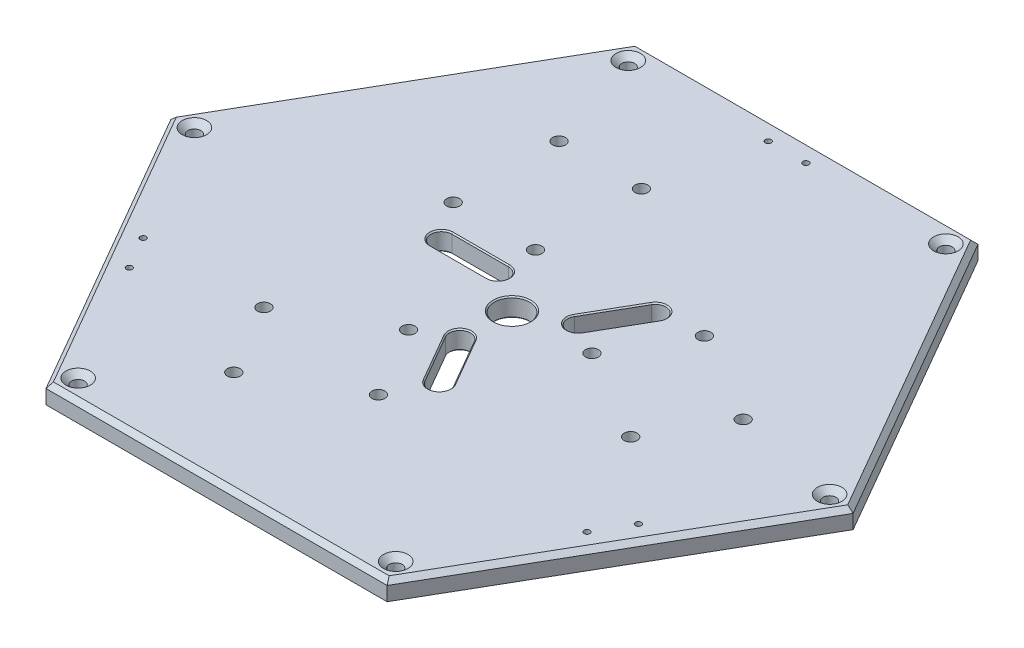
SolidWorks part; units mm, degrees
material "5052-H32"
ref_plane "Front Plane" through (0, 0, 0) normal (0, 0, 1) x (1, 0, 0)
ref_plane "Top Plane" through (0, 0, 0) normal (0, 1, 0) x (1, 0, 0)
ref_plane "Right Plane" through (0, 0, 0) normal (1, 0, 0) x (0, 0, -1)
sketch "Sketch1" plane through (0, 0, 0) normal (0, 1, 0) x (1, 0, 0)
  line L1 (72.5, 125.5737) -> (-72.5, 125.5737)
  line L2 (-72.5, 125.5737) -> (-145, 0)
  line L3 (-145, 0) -> (-72.5, -125.5737)
  line L4 (-72.5, -125.5737) -> (72.5, -125.5737)
  line L5 (72.5, -125.5737) -> (145, 0)
  line L6 (145, 0) -> (72.5, 125.5737)
  circle A0 centre (0, 0) radius 125.5737 construction
  dimension "D1" = 145
extrude "Boss-Extrude1" add sketch "Sketch1" along normal blind 8
sketch "Sketch2" plane through (0, 0, 0) normal (0, 1, 0) x (1, 0, 0)
  line L0 (0, 0) -> (108.75, 62.7868) construction
  line L1 (145, 0) -> (72.5, 125.5737) construction
  line L2 (69.5513, 20.4663) -> (52.0513, -9.8446) construction
  line L3 (69.0368, -25.4247) -> (30.0657, -2.9247) construction
  line L4 (66.5368, -29.7548) -> (27.5657, -7.2548) construction
  line L5 (53.4484, -16.4247) -> (43.4484, -33.7452) construction
  line L6 (32.5657, 1.4054) -> (71.5368, -21.0946) construction
  line L7 (71.5368, -21.0946) -> (89.0368, 9.2163) construction
  line L8 (89.0368, 9.2163) -> (50.0657, 31.7163) construction
  line L9 (50.0657, 31.7163) -> (32.5657, 1.4054) construction
  line L10 (-15.0657, -28.9054) -> (-54.0368, -51.4054) construction
  line L11 (2.4343, -59.2163) -> (-15.0657, -28.9054) construction
  line L12 (-36.5368, -81.7163) -> (2.4343, -59.2163) construction
  line L13 (-54.0368, -51.4054) -> (-36.5368, -81.7163) construction
  line L14 (-17.5, 27.5) -> (-17.5, 72.5) construction
  line L15 (-52.5, 27.5) -> (-17.5, 27.5) construction
  line L16 (-52.5, 72.5) -> (-52.5, 27.5) construction
  line L17 (-17.5, 72.5) -> (-52.5, 72.5) construction
  line L18 (43.4484, -33.7452) -> (35.6542, -29.2452) construction
  line L19 (52.0513, -9.8446) -> (43.3013, -25) construction
  line L20 (35.6542, -29.2452) -> (43.1542, -16.2548) construction
  line L21 (108.75, -62.7868) -> (0, 0) construction
  line L22 (72.5, -125.5737) -> (145, 0) construction
  point P9 (49.5513, -14.1747)
  point P18 (32.5657, 1.4054)
  point P19 (50.0657, 31.7163)
  point P20 (89.0368, 9.2163)
  point P21 (71.5368, -21.0946)
  point P31 (0, 0)
  point P33 (47.0513, -18.5048)
  point P36 (39.5513, -31.4952)
  point P39 (39.4042, -22.75)
  dimension "D1" = 45
  dimension "D2" = 35
  dimension "D4" = 5
  dimension "D5" = 5
  dimension "D6" = 50
  dimension "D7" = 20
  dimension "D8" = 9
  dimension "D3" = 3
sketch "Sketch5" plane through (0, 8, 0) normal (0, 1, 0) x (1, 0, 0)
  circle A0 centre (0, 0) radius 7.5
  dimension "D1" = 15
extrude "Cut-Extrude1" cut sketch "Sketch5" against normal through all
hole_wizard "CSK for M5 Flat Head Machine Screw1" positions "Sketch7" profile "Sketch6" countersink size "M5" standard "ANSI Metric" end condition through all
sketch "Sketch7" plane through (0, 0, 0) normal (0, -1, 0) x (-1, 0, 0)
  point P0 (52.5, 27.5)
  point P3 (17.5, 27.5)
  point P6 (17.5, 72.5)
  point P9 (52.5, 72.5)
  point P12 (-32.5657, 1.4054)
  point P15 (-71.5368, -21.0946)
  point P18 (-89.0368, 9.2163)
  point P21 (-50.0657, 31.7163)
  point P24 (15.0657, -28.9054)
  point P27 (-2.4343, -59.2163)
  point P30 (36.5368, -81.7163)
  point P33 (54.0368, -51.4054)
sketch "Sketch6" plane through (-52.5, 0, -27.5) normal (1, 0, 0) x (0, 0, -1)
  line L0 (0, 0) -> (0, 8)
  line L1 (0, 8) -> (2.75, 8)
  line L2 (2.75, 8) -> (2.75, 2.45)
  line L3 (2.75, 2.45) -> (5.2, 0)
  line L5 (5.2, 0) -> (0, 0)
  line L6 (-2.75, 2.45) -> (-5.2, 0) construction
  line L11 (0, -6.35) -> (0, 107.95) construction
  dimension "Thru Hole Dia." = 5.5
  dimension "Thru Hole Depth" = 8
  dimension "Near C'Sink Dia." = 10.4
  dimension "Near C'Sink Angle" = 90
sketch "Sketch9" plane through (0, 0, 0) normal (0, -1, 0) x (1, 0, 0)
  line L0 (30.7093, -30.1901) -> (18.7093, -9.4054) construction
  line L1 (26.8122, -32.4401) -> (14.8122, -11.6554)
  line L2 (34.6064, -27.9401) -> (22.6064, -7.1554)
  line L3 (18.7093, -9.4054) -> (36.2093, -39.7163) construction
  line L4 (89.0368, -9.2163) -> (50.0657, -31.7163) construction
  line L5 (32.5657, -1.4054) -> (71.5368, 21.0946) construction
  line L6 (50.0657, -31.7163) -> (32.5657, -1.4054) construction
  line L7 (-41.5, -11.5) -> (-17.5, -11.5) construction
  line L8 (-41.5, -7) -> (-17.5, -7)
  line L9 (-41.5, -16) -> (-17.5, -16)
  line L10 (10.7907, 41.6901) -> (-1.2093, 20.9054) construction
  line L11 (14.6878, 39.4401) -> (2.6878, 18.6554)
  line L12 (6.8936, 43.9401) -> (-5.1064, 23.1554)
  line L13 (36.2093, -39.7163) -> (50.0657, -31.7163) construction
  arc A0 (26.8122, -32.4401) -> (34.6064, -27.9401) centre (30.7093, -30.1901) ccw
  arc A1 (22.6064, -7.1554) -> (14.8122, -11.6554) centre (18.7093, -9.4054) ccw
  arc A2 (-41.5, -7) -> (-41.5, -16) centre (-41.5, -11.5) ccw
  arc A3 (-17.5, -16) -> (-17.5, -7) centre (-17.5, -11.5) ccw
  arc A4 (14.6878, 39.4401) -> (6.8936, 43.9401) centre (10.7907, 41.6901) ccw
  arc A5 (-5.1064, 23.1554) -> (2.6878, 18.6554) centre (-1.2093, 20.9054) ccw
  point P2 (24.7093, -19.7977)
  point P19 (-29.5, -11.5)
  point P26 (4.7907, 31.2977)
  point P31 (0, 0)
  dimension "D1" = 16
  dimension "D2" = 9
  dimension "D3" = 24
  dimension "D5" = 23
  dimension "D4" = 3
extrude "Cut-Extrude3" cut sketch "Sketch9" against normal through all
sketch "Sketch10" plane through (0, 8, 0) normal (0, 1, 0) x (1, 0, 0)
  line L0 (145, 0) -> (0, 0) construction
  point P4 (135, 0)
  point P7 (67.5, -116.9134)
  point P8 (-67.5, -116.9134)
  point P9 (-135, 0)
  point P10 (-67.5, 116.9134)
  point P11 (67.5, 116.9134)
  point P12 (0, 0)
  dimension "D2" = 10
  dimension "D1" = 6
hole_wizard "CSK for M5 Flat Head Machine Screw2" positions "Sketch14" profile "Sketch13" countersink size "M5" standard "ANSI Metric"
sketch "Sketch14" plane through (0, 8, 0) normal (0, 1, 0) x (1, 0, 0)
  point P0 (-135, 0)
  point P3 (-67.5, -116.9134)
  point P6 (67.5, -116.9134)
  point P9 (135, 0)
  point P12 (67.5, 116.9134)
  point P15 (-67.5, 116.9134)
sketch "Sketch13" plane through (-135, 8, 0) normal (1, 0, 0) x (0, 0, 1)
  line L0 (0, 0) -> (0, 11.6524)
  line L1 (0, 11.6524) -> (2.75, 10)
  line L2 (2.75, 10) -> (2.75, 2.45)
  line L3 (2.75, 2.45) -> (5.2, 0)
  line L5 (5.2, 0) -> (0, 0)
  line L6 (-2.75, 2.45) -> (-5.2, 0) construction
  line L10 (0, 11.6524) -> (-2.75, 10) construction
  line L11 (0, -6.35) -> (0, 107.95) construction
  dimension "Hole Dia." = 5.5
  dimension "Hole Depth" = 10
  dimension "Near C'Sink Dia." = 10.4
  dimension "Near C'Sink Angle" = 90
  dimension "Drill Angle" = 118
chamfer "Chamfer1" distance 0.5 angle 45 24 edges at (-29.5, 0, -16) (-13, 0, -11.5) (-46, 0, -11.5) (-29.5, 0, -7) (20.8122, 0, -22.0477) (32.9593, 0, -34.0872) (16.4593, 0, -5.5083) (28.6064, 0, -17.5477) (0.8936, 0, 33.5477) (-3.4593, 0, 17.0083) (13.0407, 0, 45.5872) (8.6878, 0, 29.0477) (-29.5, 8, -16) (-13, 8, -11.5) (-46, 8, -11.5) (-29.5, 8, -7) (20.8122, 8, -22.0477) (32.9593, 8, -34.0872) (16.4593, 8, -5.5083) (28.6064, 8, -17.5477) (0.8936, 8, 33.5477) (-3.4593, 8, 17.0083) (13.0407, 8, 45.5872) (8.6878, 8, 29.0477)
sketch "Sketch8" plane through (0, 0, 0) normal (0, -1, 0) x (1, 0, 0)
  line L0 (104.25, 70.5811) -> (113.25, 54.9926)
  line L1 (104.25, 70.5811) -> (66.9471, 49.0442)
  line L2 (113.25, 54.9926) -> (75.9471, 33.4558)
  line L3 (66.9471, 49.0442) -> (75.9471, 33.4558)
  line L4 (72.5, 125.5737) -> (145, 0) construction
  line L5 (108.75, 62.7868) -> (0, 0) construction
  line L7 (9, -125.5737) -> (-9, -125.5737)
  line L8 (9, -125.5737) -> (9, -82.5)
  line L9 (-9, -125.5737) -> (-9, -82.5)
  line L10 (9, -82.5) -> (-9, -82.5)
  line L11 (-113.25, 54.9926) -> (-104.25, 70.5811)
  line L12 (-113.25, 54.9926) -> (-75.9471, 33.4558)
  line L13 (-104.25, 70.5811) -> (-66.9471, 49.0442)
  line L14 (-75.9471, 33.4558) -> (-66.9471, 49.0442)
  circle A0 centre (0, 0) radius 7.5 construction
  point P6 (108.75, 62.7868)
  point P22 (0, 0)
  dimension "D1" = 18
  dimension "D2" = 10
  dimension "D3" = 3
extrude "Cut-Extrude2" [suppressed] cut sketch "Sketch8" against normal through all
chamfer "Chamfer3" distance 0.5 angle 45 2 edges at (0, 8, 7.5) (0, 0, 7.5)
chamfer "Chamfer4" distance 2 angle 45 6 edges at (0, 8, 125.5737) (108.75, 8, 62.7868) (108.75, 8, -62.7868) (0, 8, -125.5737) (-108.75, 8, -62.7868) (-108.75, 8, 62.7868)
sketch "Sketch15" plane through (0, 8, 0) normal (0, 1, 0) x (1, 0, 0)
  line L0 (0, 0) -> (107.0179, -61.7868) construction
  line L1 (71.3453, -123.5737) -> (142.6906, 0) construction
  line L2 (97.25, -65.3849) -> (105.25, -51.5285) construction
  circle A0 centre (97.25, -65.3849) radius 1.5
  circle A1 centre (105.25, -51.5285) radius 1.5
  circle A2 centre (-105.25, -51.5285) radius 1.5
  circle A3 centre (-97.25, -65.3849) radius 1.5
  circle A4 centre (8, 116.9134) radius 1.5
  circle A5 centre (-8, 116.9134) radius 1.5
  circle A6 centre (67.5, -116.9134) radius 2.75 construction
  point P7 (101.25, -58.4567)
  point P21 (0, 0)
  dimension "D2" = 3
  dimension "D1" = 16
  dimension "D4" = 0
  dimension "D3" = 3
hole_wizard "M3x0.5 Tapped Hole1" positions "Sketch17" profile "Sketch16" tap size "M3x0.5" standard "ANSI Metric" end condition through all
sketch "Sketch17" plane through (0, 8, 0) normal (0, 1, 0) x (1, 0, 0)
  point P0 (97.25, -65.3849)
  point P3 (105.25, -51.5285)
  point P6 (8, 116.9134)
  point P9 (-8, 116.9134)
  point P12 (-105.25, -51.5285)
  point P15 (-97.25, -65.3849)
sketch "Sketch16" plane through (97.25, 8, 65.3849) normal (1, 0, 0) x (0, 0, 1)
  line L0 (0, 0) -> (0, 8)
  line L1 (0, 8) -> (1.25, 8)
  line L2 (1.25, 8) -> (1.25, 0)
  line L5 (1.25, 0) -> (0, 0)
  line L11 (0, -6.35) -> (0, 107.95) construction
  dimension "Thru Tap Drill Dia." = 2.5
  dimension "Thru Tap Drill Depth" = 8
cosmetic thread "Hole Thread1" parameters "D2"=3
cosmetic thread "Hole Thread2" parameters "D2"=3
cosmetic thread "Hole Thread3" parameters "D2"=3
cosmetic thread "Hole Thread4" parameters "D2"=3
cosmetic thread "Hole Thread5" parameters "D2"=3
cosmetic thread "Hole Thread6" parameters "D2"=3
